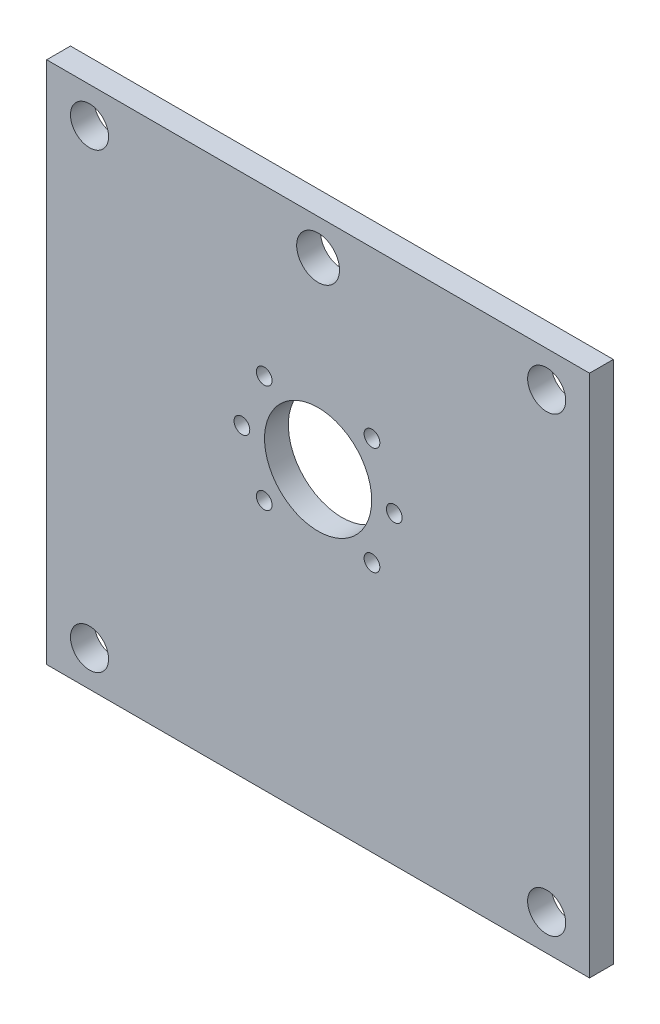
SolidWorks part; units mm, degrees
ref_plane "前视基准面" through (0, 0, 0) normal (0, 0, 1) x (1, 0, 0)
ref_plane "上视基准面" through (0, 0, 0) normal (0, 1, 0) x (1, 0, 0)
ref_plane "右视基准面" through (0, 0, 0) normal (1, 0, 0) x (0, 0, -1)
sketch "草图1" plane through (0, 0, 0) normal (0, 0, 1) x (1, 0, 0)
  line L1 (-57, 55) -> (57, 55)
  line L2 (-57, 55) -> (-57, -55)
  line L3 (-57, -55) -> (57, -55)
  line L4 (57, 55) -> (57, -55)
  line L5 (-57, 55) -> (57, -55) construction
  line L6 (-57, -55) -> (57, 55) construction
  circle A1 centre (0, 9) radius 11.25
  point P0 (0, 0)
  dimension "D6" = 46
  dimension "D7" = 22.5
  dimension "D1" = 110
  dimension "D2" = 114
extrude "凸台-拉伸1" add sketch "草图1" along normal blind 5
sketch "草图2" plane through (0, 0, 5) normal (0, 0, 1) x (1, 0, 0)
  line L0 (57, 55) -> (-57, 55) construction
  line L1 (-57, 55) -> (-57, -55) construction
  circle A0 centre (-48, 47.5) radius 4
  dimension "D1" = 7.5
  dimension "D2" = 9
  dimension "D3" = 8
extrude "切除-拉伸1" cut sketch "草图2" against normal through all
mirror "镜向1" about plane through (0, 0, 0) normal (0, 1, 0) of "切除-拉伸1"
mirror "镜向2" about plane through (0, 0, 0) normal (1, 0, 0) of "镜向1", "切除-拉伸1"
sketch "草图3" plane through (0, 0, 5) normal (0, 0, 1) x (1, 0, 0)
  line L0 (57, 55) -> (-57, 55) construction
  circle A0 centre (0, 47.5) radius 4.5
  dimension "D1" = 7.5
  dimension "D2" = 9
sketch "草图5" plane through (0, 0, 5) normal (0, 0, 1) x (1, 0, 0)
  line L0 (-1000, 9) -> (49000, 9) construction
  line L1 (0, -991) -> (0, 49009) construction
  circle A0 centre (0, 9) radius 16
  circle A1 centre (-16, 9) radius 2
  circle A2 centre (-11.3137, -2.3137) radius 2
  circle A3 centre (0, -7) radius 2
  circle A4 centre (11.3137, -2.3137) radius 2
  circle A5 centre (16, 9) radius 2
  circle A6 centre (11.3137, 20.3137) radius 2
  circle A7 centre (0, 25) radius 2
  circle A8 centre (-11.3137, 20.3137) radius 2
  point P26 (0, 9)
  dimension "D1" = 8
hole_wizard "M4 螺纹孔的螺纹孔钻头2" positions "3D草图3" profile "草图7" hole size "M4" standard "GB" end condition through all
sketch3d "3D草图3"
  line L0 (-1000, 9, 5) -> (49000, 9, 5) construction
  circle A0 centre (0, 9, 5) radius 16 construction
  point P0 (-16, 9, 5)
  point P4 (0, 9, 21)
sketch "草图7" plane through (-16, 9, 5) normal (1, 0, 0) x (0, -1, 0)
  line L0 (0, 0) -> (0, 5)
  line L1 (0, 5) -> (1.65, 5)
  line L2 (1.65, 5) -> (1.65, 0)
  line L5 (1.65, 0) -> (0, 0)
  line L11 (0, -6.35) -> (0, 107.95) construction
  dimension "通孔孔直径" = 3.3
  dimension "通孔孔深度" = 5
hole_wizard "M4 螺纹孔的螺纹孔钻头3" positions "3D草图4" profile "草图8" hole size "M4" standard "GB" end condition through all
sketch3d "3D草图4"
  point P0 (-11.3137, 20.3137, 5)
  point P3 (-11.3137, -2.3137, 5)
sketch "草图8" plane through (-11.3137, 20.3137, 5) normal (1, 0, 0) x (0, -1, 0)
  line L0 (0, 0) -> (0, 5)
  line L1 (0, 5) -> (1.65, 5)
  line L2 (1.65, 5) -> (1.65, 0)
  line L5 (1.65, 0) -> (0, 0)
  line L11 (0, -6.35) -> (0, 107.95) construction
  dimension "通孔孔直径" = 3.3
  dimension "通孔孔深度" = 5
hole_wizard "M4 螺纹孔的螺纹孔钻头4" positions "3D草图5" profile "草图9" hole size "M4" standard "GB" end condition through all
sketch3d "3D草图5"
  point P0 (11.3137, 20.3137, 5)
  point P3 (16, 9, 5)
  point P6 (11.3137, -2.3137, 5)
sketch "草图9" plane through (11.3137, 20.3137, 5) normal (1, 0, 0) x (0, -1, 0)
  line L0 (0, 0) -> (0, 5)
  line L1 (0, 5) -> (1.65, 5)
  line L2 (1.65, 5) -> (1.65, 0)
  line L5 (1.65, 0) -> (0, 0)
  line L11 (0, -6.35) -> (0, 107.95) construction
  dimension "通孔孔直径" = 3.3
  dimension "通孔孔深度" = 5
extrude "切除-拉伸2" cut sketch "草图3" against normal through all
